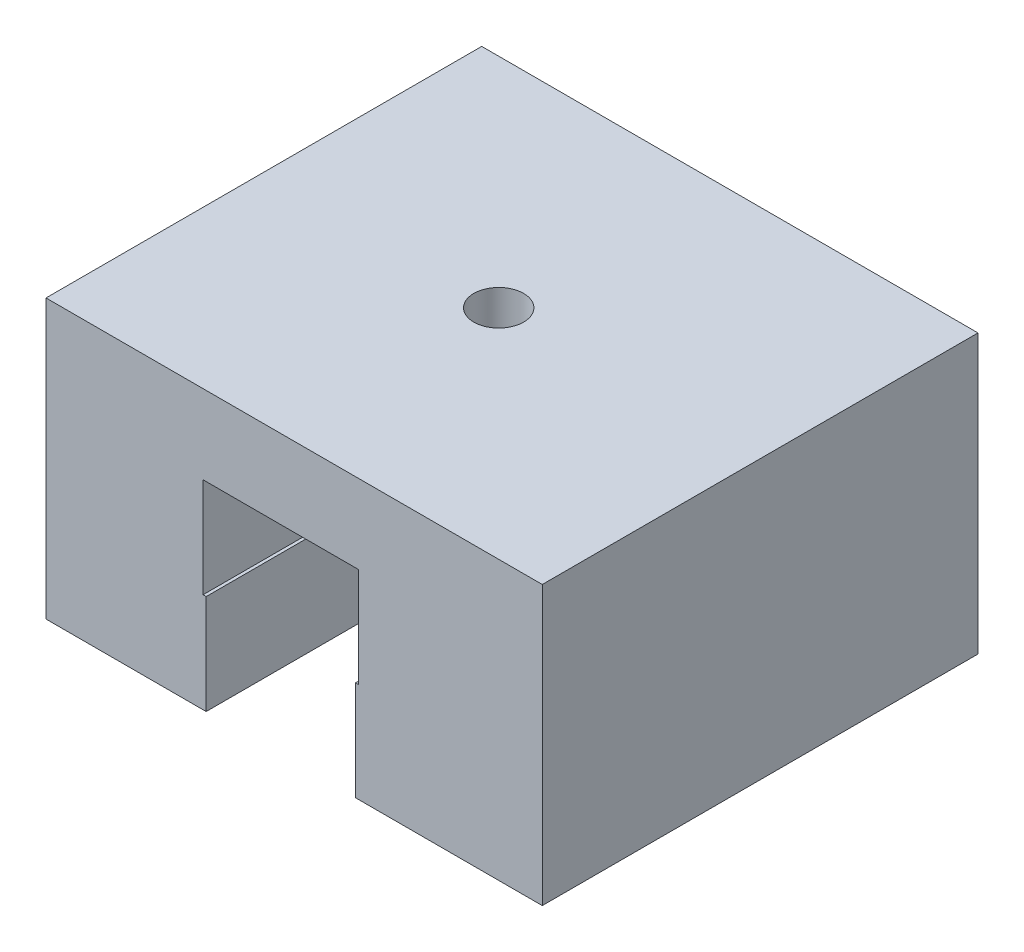
SolidWorks part; units mm, degrees
ref_plane "Front Plane" through (0, 0, 0) normal (0, 0, 1) x (1, 0, 0)
ref_plane "Top Plane" through (0, 0, 0) normal (0, 1, 0) x (1, 0, 0)
ref_plane "Right Plane" through (0, 0, 0) normal (1, 0, 0) x (0, 0, -1)
sketch "Sketch1" plane through (0, 0, 0) normal (0, 1, 0) x (1, 0, 0)
  line L0 (0, 0) -> (-200, 0) construction
  line L1 (-200, 0) -> (-400, 0) construction
  dimension "D1" = 200
  dimension "D2" = 200
sketch "Sketch2" plane through (0, 0, 0) normal (0, 1, 0) x (1, 0, 0)
  line L1 (-200, -17.5) -> (0, -17.5)
  line L2 (-200, -17.5) -> (-200, 17.5)
  line L3 (-200, 17.5) -> (0, 17.5)
  line L4 (0, -17.5) -> (0, 17.5)
  point P4 (-200, 0)
  dimension "D1" = 35
extrude "Boss-Extrude1" add sketch "Sketch2" along normal blind 30 contours L1 L4 L3 L2
sketch "Sketch3" plane through (0, 0, 0) normal (0, -1, 0) x (1, 0, 0)
  line L0 (0, 0) -> (-21, 0) construction
  line L1 (0, 0) -> (-200, 0) construction
  circle A0 centre (-21, 0) radius 6
  dimension "D2" = 12
  dimension "D1" = 21
extrude "Cut-Extrude1" cut sketch "Sketch3" against normal through all
sketch "Sketch4" plane through (0, 30, 0) normal (0, 1, 0) x (1, 0, 0)
  line L0 (0, -17.5) -> (0, 17.5) construction
  line L1 (-14.75, 3.6084) -> (-21, 7.2169)
  line L2 (-21, 7.2169) -> (-27.25, 3.6084)
  line L3 (-27.25, 3.6084) -> (-27.25, -3.6084)
  line L4 (-27.25, -3.6084) -> (-21, -7.2169)
  line L5 (-21, -7.2169) -> (-14.75, -3.6084)
  line L6 (-14.75, -3.6084) -> (-14.75, 3.6084)
  line L7 (-27.25, 0) -> (-14.75, 0)
  circle A0 centre (-21, 0) radius 6.25 construction
  point P13 (0, 0)
  dimension "D1" = 12.5
extrude "Cut-Extrude2" cut sketch "Sketch4" against normal blind 22 contours L1 L2 L3 L4 L5 L6
sketch "Sketch5" plane through (0, 0, 0) normal (1, 0, 0) x (0, 0, -1)
  line L0 (0, 8) -> (0, 1) construction
  line L1 (-3.6084, 8) -> (3.6084, 8) construction
  line L2 (0, 1) -> (0, -2.0977) construction
  line L3 (2.5, 1) -> (2.5, -2.0977)
  line L4 (-2.5, 1) -> (-2.5, -2.0977)
  arc A0 (2.5, 1) -> (-2.5, 1) centre (0, 1) ccw
  arc A1 (-2.5, -2.0977) -> (2.5, -2.0977) centre (0, -2.0977) ccw
  point P5 (0, -0.5488)
  dimension "D1" = 7
  dimension "D2" = 5
sketch "Sketch6" plane through (0, 0, 0) normal (1, 0, 0) x (0, 0, -1)
  line L0 (0, 8) -> (0, 16) construction
  line L1 (-3.6084, 8) -> (3.6084, 8) construction
  line L2 (-17.5, 30) -> (17.5, 30) construction
  line L3 (-11.0435, 16) -> (11.453, 16)
  line L4 (-11.0435, 16) -> (-11.0435, 30)
  line L5 (-11.0435, 30) -> (11.453, 30)
  line L6 (11.453, 16) -> (11.453, 30)
  dimension "D1" = 8
extrude "Boss-Extrude3" add sketch "Sketch6" against normal blind 38
sketch "Sketch7" plane through (0, 0, 17.5) normal (0, 0, 1) x (1, 0, 0)
  line L0 (-21, 16) -> (-14.75, 16) construction
  line L1 (-27.25, 16) -> (-21, 16) construction
  line L2 (-27.25, 8) -> (-27.25, 16) construction
  line L3 (-14.75, 8) -> (-14.75, 16) construction
  line L4 (-15, 0) -> (-15, 8) construction
  line L5 (-27, 8) -> (-27, 0) construction
  line L6 (-21, 16) -> (-14.75, 16)
  line L7 (-27.25, 16) -> (-21, 16)
  line L8 (-27.25, 8) -> (-27.25, 16)
  line L9 (-14.75, 8) -> (-14.75, 16)
  line L10 (-15, 0) -> (-15, 8)
  line L11 (-27, 8) -> (-27, 0)
  line L12 (-27.25, 8) -> (-27, 8)
  line L13 (-15, 8) -> (-14.75, 8)
  line L14 (-27, 0) -> (-15, 0)
extrude "Cut-Extrude4" cut sketch "Sketch7" against normal up to vertex (17.5 mm away) up to point (-14.75, 30, 0)
sketch "Sketch9" plane through (0, 30, 0) normal (0, 1, 0) x (1, 0, 0)
  line L0 (-27.25, 3.6084) -> (-14.75, -3.6084) construction
  line L1 (-27.25, -3.6084) -> (-14.75, 3.6084) construction
  line L6 (-14.75, 3.6084) -> (-21, 7.2169)
  line L7 (-21, 7.2169) -> (-27.25, 3.6084)
  line L8 (-27.25, 3.6084) -> (-27.25, -3.6084)
  line L9 (-27.25, -3.6084) -> (-21, -7.2169)
  line L10 (-21, -7.2169) -> (-14.75, -3.6084)
  line L11 (-14.75, -3.6084) -> (-14.75, 3.6084)
  line L12 (-14.75, 3.6084) -> (-21, 7.2169) construction
  line L13 (-21, 7.2169) -> (-27.25, 3.6084) construction
  line L14 (-27.25, 3.6084) -> (-27.25, -3.6084) construction
  line L15 (-27.25, -3.6084) -> (-21, -7.2169) construction
  line L16 (-21, -7.2169) -> (-14.75, -3.6084) construction
  line L17 (-14.75, -3.6084) -> (-14.75, 3.6084) construction
  circle A0 centre (-21, 0) radius 2
  dimension "D2" = 4
  dimension "D1" = 0
extrude "Cut-Extrude5" cut sketch "Sketch9" against normal blind 38
sketch "Sketch10" plane through (-200, 0, 0) normal (-1, 0, 0) x (0, 0, 1)
  line L0 (-17.5, 30) -> (17.5, 0) construction
  line L2 (-6.5, 8.5) -> (6.5, 8.5) construction
  line L3 (-6.5, 8.5) -> (-6.5, 21.5) construction
  line L4 (-6.5, 21.5) -> (6.5, 21.5) construction
  line L5 (6.5, 8.5) -> (6.5, 21.5) construction
  line L6 (-6.5, 8.5) -> (6.5, 21.5) construction
  line L7 (-6.5, 21.5) -> (6.5, 8.5) construction
  circle A0 centre (6.5, 21.5) radius 2.25
  circle A1 centre (6.5, 8.5) radius 2.25
  circle A2 centre (-6.5, 8.5) radius 2.25
  circle A3 centre (-6.5, 21.5) radius 2.25
  point P4 (0, 15)
  dimension "D3" = 4.5
  dimension "D1" = 13
  dimension "D2" = 13
extrude "Cut-Extrude6" cut sketch "Sketch10" against normal blind 20
sketch "Sketch11" plane through (0, 30, 0) normal (0, 1, 0) x (1, 0, 0)
  line L0 (-200, 0) -> (-194, 0) construction
  line L1 (0, 0) -> (-200, 0) construction
  line L2 (-194, 0) -> (-194, -8.75) construction
  line L3 (-200, -8.75) -> (-180, -8.75) construction
  line L4 (-194, -8.75) -> (-190, -8.75) construction
  line L5 (-194, 0) -> (-194, 8.75) construction
  line L6 (-180, 8.75) -> (-200, 8.75) construction
  line L7 (-194, 8.75) -> (-190, 8.75) construction
  dimension "D1" = 6
  dimension "D2" = 4
  dimension "D3" = 4
sketch "Sketch12" plane through (0, 30, 0) normal (0, 1, 0) x (1, 0, 0)
  line L0 (-194, -8.75) -> (-194, -4.375) construction
  line L1 (-194, 0) -> (-194, -8.75) construction
  line L2 (-194, -10.3125) -> (-194, -2.8125)
  line L3 (-194, 4.375) -> (-194, 8.75) construction
  line L4 (-194, 0) -> (-194, 8.75) construction
  line L5 (-194, 2.8125) -> (-194, 10.3125)
  line L6 (-194, 10.3125) -> (-189.5, 10.3125)
  line L7 (-189.5, 10.3125) -> (-189.5, 2.8125)
  line L8 (-189.5, 2.8125) -> (-194, 2.8125)
  line L9 (-194, -2.8125) -> (-189.5, -2.8125)
  line L10 (-189.5, -2.8125) -> (-189.5, -10.3125)
  line L11 (-189.5, -10.3125) -> (-194, -10.3125)
  point P8 (-194, -6.5625)
  point P16 (-194, 6.5625)
  dimension "D1" = 7.5
  dimension "D2" = 4.5
extrude "Cut-Extrude7" cut sketch "Sketch12" against normal blind 46
sketch "Sketch14" plane through (0, 0, 17.5) normal (0, 0, 1) x (1, 0, 0)
  line L1 (-39.8658, 22.3405) -> (9.5268, 22.3405)
  line L2 (-39.8658, 22.3405) -> (-39.8658, -15.5316)
  line L3 (-39.8658, -15.5316) -> (9.5268, -15.5316)
  line L4 (9.5268, 22.3405) -> (9.5268, -15.5316)
  line L5 (-217.6837, 72.0684) -> (187.6837, 72.0684)
  line L6 (-217.6837, 72.0684) -> (-217.6837, -72.0684)
  line L7 (-217.6837, -72.0684) -> (187.6837, -72.0684)
  line L8 (187.6837, 72.0684) -> (187.6837, -72.0684)
  line L9 (-217.6837, 72.0684) -> (187.6837, -72.0684) construction
  line L10 (-217.6837, -72.0684) -> (187.6837, 72.0684) construction
  point P4 (-15, 0)
  line M4 (0, 0) -> (0, 30)
  line M5 (0, 30) -> (-200, 30)
  line M6 (-200, 30) -> (-200, 0)
  line M7 (-200, 0) -> (-27, 0)
extrude "Cut-Extrude9" cut sketch "Sketch14" against normal through all contours L8 L5 L6 L7 L1 L4 L3 L2 M7 M6 M5 M4 | L2 L1 M4 M5 M6 M7
equation "\"2.5c\"=10"
